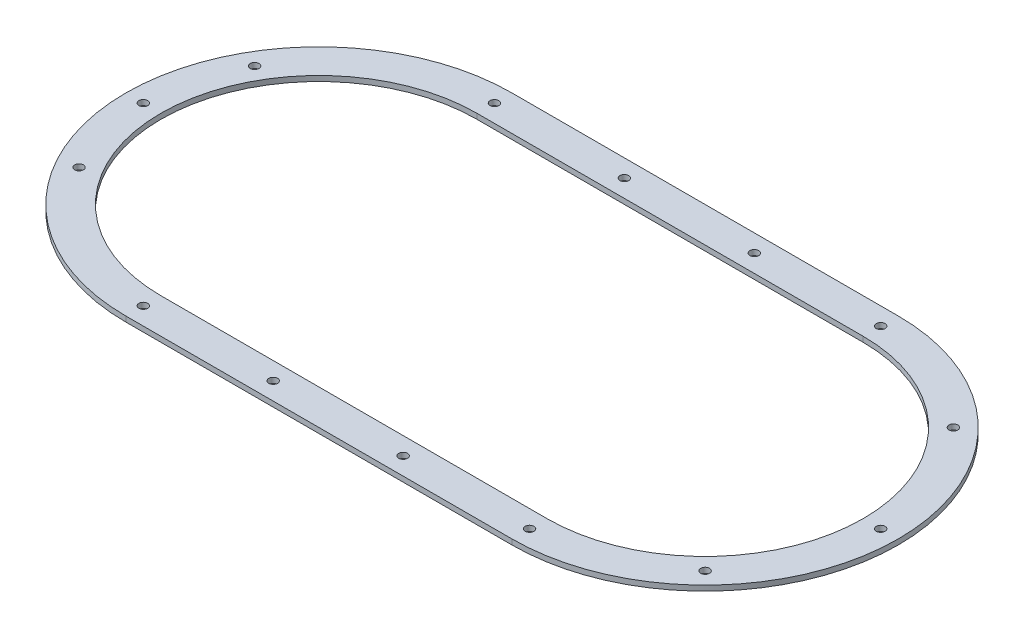
SolidWorks part; units mm, degrees
ref_plane "Plano frontal" through (0, 0, 0) normal (0, 0, 1) x (1, 0, 0)
ref_plane "Plano superior" through (0, 0, 0) normal (0, 1, 0) x (1, 0, 0)
ref_plane "Plano direito" through (0, 0, 0) normal (1, 0, 0) x (0, 0, -1)
sketch "Esboço1" plane through (0, 0, 0) normal (0, 1, 0) x (1, 0, 0)
  line L0 (68.5445, 235.0105) -> (288.5445, 235.0105)
  line L1 (68.5445, 215.0105) -> (288.5445, 215.0105)
  line L2 (68.5445, 35.0105) -> (288.5445, 35.0105)
  line L3 (68.5445, 15.0105) -> (288.5445, 15.0105)
  line L4 (68.5445, 25.0105) -> (288.5445, 25.0105)
  line L5 (68.5445, 225.0105) -> (288.5445, 225.0105)
  arc A0 (68.5445, 235.0105) -> (68.5445, 15.0105) centre (68.5445, 125.0105) ccw
  arc A1 (68.5445, 225.0105) -> (68.5445, 25.0105) centre (68.5445, 125.0105) ccw
  arc A2 (68.5445, 215.0105) -> (68.5445, 35.0105) centre (68.5445, 125.0105) ccw
  arc A6 (288.5445, 15.0105) -> (288.5445, 235.0105) centre (288.5445, 125.0105) ccw
  arc A7 (288.5445, 25.0105) -> (288.5445, 225.0105) centre (288.5445, 125.0105) ccw
  arc A8 (288.5445, 35.0105) -> (288.5445, 215.0105) centre (288.5445, 125.0105) ccw
  circle A9 centre (68.5445, 225.0105) radius 2.5
  circle A10 centre (68.5445, 25.0105) radius 2.5
  circle A11 centre (288.5445, 25.0105) radius 2.5
  circle A12 centre (288.5445, 225.0105) radius 2.5
  circle A13 centre (-18.0581, 175.0105) radius 2.5
  circle A14 centre (-31.4555, 125.0105) radius 2.5
  circle A15 centre (-18.0581, 75.0105) radius 2.5
  circle A16 centre (359.2551, 54.2998) radius 2.5
  circle A17 centre (388.5445, 125.0105) radius 2.5
  circle A18 centre (359.2551, 195.7211) radius 2.5
  circle A19 centre (142.5445, 25.0105) radius 2.5
  circle A20 centre (216.5445, 25.0105) radius 2.5
  circle A22 centre (142.5445, 225.0105) radius 2.5
  circle A23 centre (216.5445, 225.0105) radius 2.5
  point P16 (68.5445, 28.3042)
  point P19 (292.1892, 25.0769)
  point P21 (285.003, 225.0105)
  point P23 (6.1632, 203.1678)
  point P26 (-29.5419, 125.0105)
  point P27 (-31.4555, 125.0105)
  point P30 (-3.0409, 55.1854)
  point P33 (352.2509, 47.9294)
  point P36 (388.5445, 125.0105)
  point P39 (358.0022, 196.9522)
  point P42 (126.8433, 25.0105)
  point P45 (186.4565, 25.0105)
  point P48 (247.3587, 25.0105)
  point P51 (126.8433, 225.0105)
  point P54 (186.4565, 225.0105)
  point P57 (247.3587, 225.0105)
  dimension "D1" = 220
  dimension "D2" = 200
  dimension "D3" = 180
  dimension "D4" = 5
  dimension "D5" = 220
  dimension "D6" = 74
  dimension "D7" = 74
  dimension "D8" = 74
  dimension "D9" = 74
  dimension "D10" = 30
  dimension "D11" = 45
  dimension "D12" = 30
  dimension "D13" = 45
extrude "Ressalto-extrusão2" add sketch "Esboço1" along normal blind 3 contours L3 A6 L0 A0 A23 L5 A12 A7 A18 A17 A16 A11 L4 A20 A19 A10 A1 A15 A14 A13 A9 A22 | A23 L5 A22 A9 A1 A13 A14 A15 A10 L4 A19 A20 A11 A7 A16 A17 A18 A12 A8 L2 A2 L1
